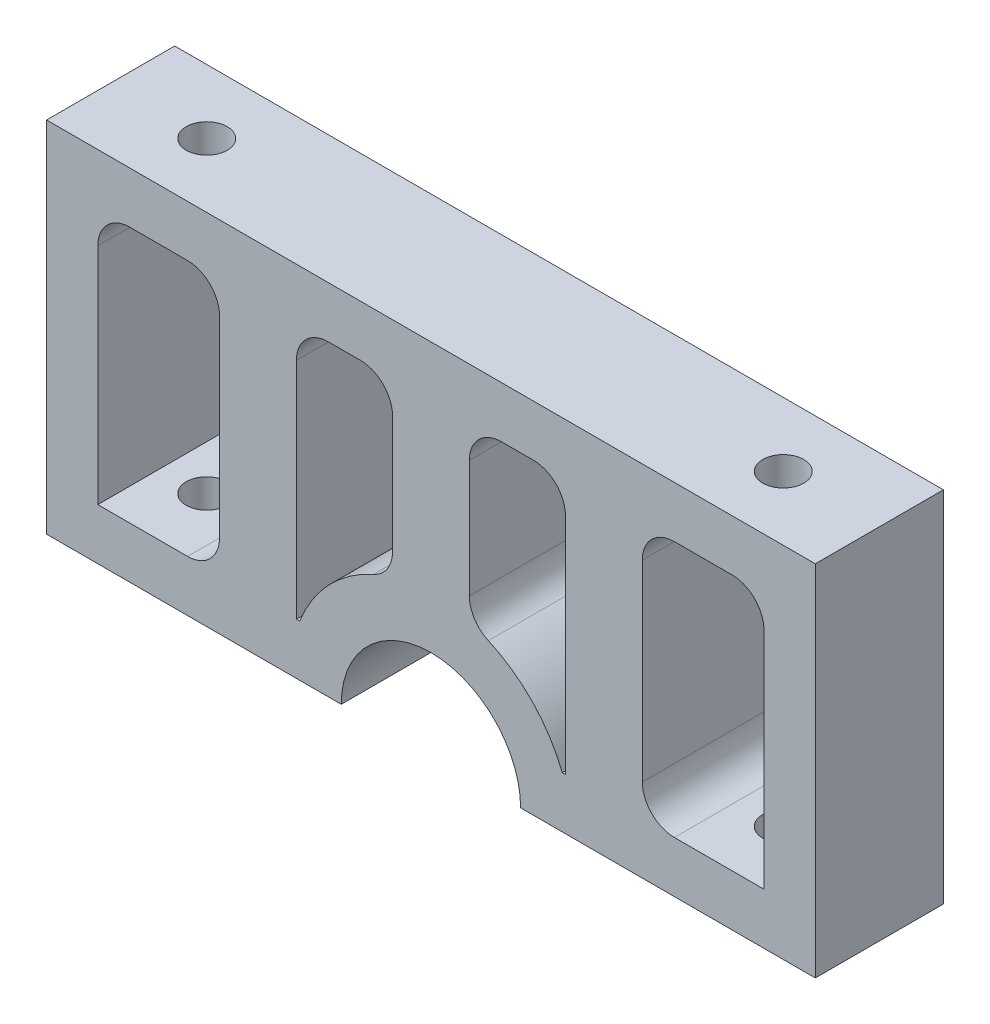
SolidWorks part; units mm, degrees
ref_plane "Front" through (0, 0, 0) normal (0, 0, 1) x (1, 0, 0)
ref_plane "Top" through (0, 0, 0) normal (0, 1, 0) x (1, 0, 0)
ref_plane "Right" through (0, 0, 0) normal (1, 0, 0) x (0, 0, -1)
sketch "ｽｹｯﾁ1" plane through (0, 0, 0) normal (0, 0, 1) x (1, 0, 0)
  line L1 (30, -28) -> (-30, -28)
  line L2 (30, -28) -> (30, 28)
  line L3 (30, 28) -> (-30, 28)
  line L4 (-30, -28) -> (-30, 28)
  line L5 (0, 28) -> (0, -28) construction
  line L6 (30, 0) -> (-30, 0)
  circle A0 centre (0, 0) radius 7
  point P0 (0, 0)
  dimension "D3" = 14
  dimension "D1" = 60
  dimension "D2" = 56
extrude "ﾎﾞｽ - 押し出し1" add sketch "ｽｹｯﾁ1" along normal blind 10 contours L5 L3 L4 L6 A0 | L3 L5 A0 L6 L2
sketch "ｽｹｯﾁ2" plane through (0, 0, 10) normal (0, 0, 1) x (1, 0, 0)
  line L0 (26, 24) -> (-26, 24)
  line L1 (-26, 24) -> (-26, 4)
  line L2 (-26, 4) -> (-10.247, 4)
  line L3 (10.247, 4) -> (26, 4)
  line L4 (26, 4) -> (26, 24)
  line L5 (7, 0) -> (30, 0)
  line L6 (30, 0) -> (30, 28)
  line L7 (30, 28) -> (-30, 28)
  line L8 (-30, 28) -> (-30, 0)
  line L9 (-30, 0) -> (-7, 0)
  line L10 (7, 0) -> (30, 0)
  line L11 (30, 0) -> (30, 28)
  line L12 (30, 28) -> (-30, 28)
  line L13 (-30, 28) -> (-30, 0)
  line L14 (-30, 0) -> (-7, 0)
  line L16 (3, 0) -> (-3, 0)
  line L17 (3, 0) -> (3, 24)
  line L18 (3, 24) -> (-3, 24)
  line L19 (-3, 0) -> (-3, 24)
  line L20 (0, 24) -> (0, 0) construction
  line L21 (3, 12) -> (-3, 12) construction
  line L22 (-10.5, 0) -> (-16.5, 0)
  line L23 (-10.5, 0) -> (-10.5, 28)
  line L24 (-10.5, 28) -> (-16.5, 28)
  line L25 (-16.5, 0) -> (-16.5, 28)
  line L26 (-13.5, 28) -> (-13.5, 0) construction
  line L27 (-10.5, 14) -> (-16.5, 14) construction
  line L28 (16.5, 0) -> (10.5, 0)
  line L29 (16.5, 0) -> (16.5, 28)
  line L30 (16.5, 28) -> (10.5, 28)
  line L31 (10.5, 0) -> (10.5, 28)
  line L32 (13.5, 28) -> (13.5, 0) construction
  line L33 (16.5, 14) -> (10.5, 14) construction
  arc A0 (10.247, 4) -> (-10.247, 4) centre (0, 0) ccw
  arc A1 (7, 0) -> (-7, 0) centre (0, 0) ccw
  arc A2 (7, 0) -> (-7, 0) centre (0, 0) ccw
  point P14 (0, 12)
  point P18 (-13.5, 14)
  point P22 (13.5, 14)
  dimension "D3" = 6
  dimension "D4" = 0
  dimension "D5" = 0
  dimension "D6" = 6
  dimension "D7" = 6
  dimension "D8" = 0
  dimension "D9" = 0
  dimension "7.5" = 7.5
  dimension "D11" = 7.5
  dimension "D1" = 0
  dimension "D2" = 4
extrude "ｶｯﾄ - 押し出し2" cut sketch "ｽｹｯﾁ2" against normal blind 15 contours L29 L3 L4 L0 | A0 L31 L0 L17 | A0 L19 L0 L23 | L2 L25 L0 L1
fillet "ﾌｨﾚｯﾄ1" radius 2.5 12 edges at (-16.5, 4, 5) (-3, 10.583, 5) (16.5, 4, 5) (3, 10.583, 5) (16.5, 24, 5) (3, 24, 5) (-10.5, 24, 5) (-26, 24, 5) (26, 24, 5) (10.5, 24, 5) (-3, 24, 5) (-16.5, 24, 5)
sketch "ｽｹｯﾁ3" plane through (0, 28, 0) normal (0, 1, 0) x (1, 0, 0)
  line L0 (30, 0) -> (-30, 0) construction
  line L1 (-30, -10) -> (-30, 0) construction
  line L2 (30, -10) -> (30, 0) construction
  circle A0 centre (-22.5, -5) radius 1.6
  circle A1 centre (22.5, -5) radius 1.6
  dimension "D1" = 3.2
  dimension "D2" = 3.2
  dimension "D3" = 5
  dimension "D4" = 5
  dimension "D5" = 7.5
  dimension "D6" = 7.5
extrude "ｶｯﾄ - 押し出し1" cut sketch "ｽｹｯﾁ3" against normal through all
